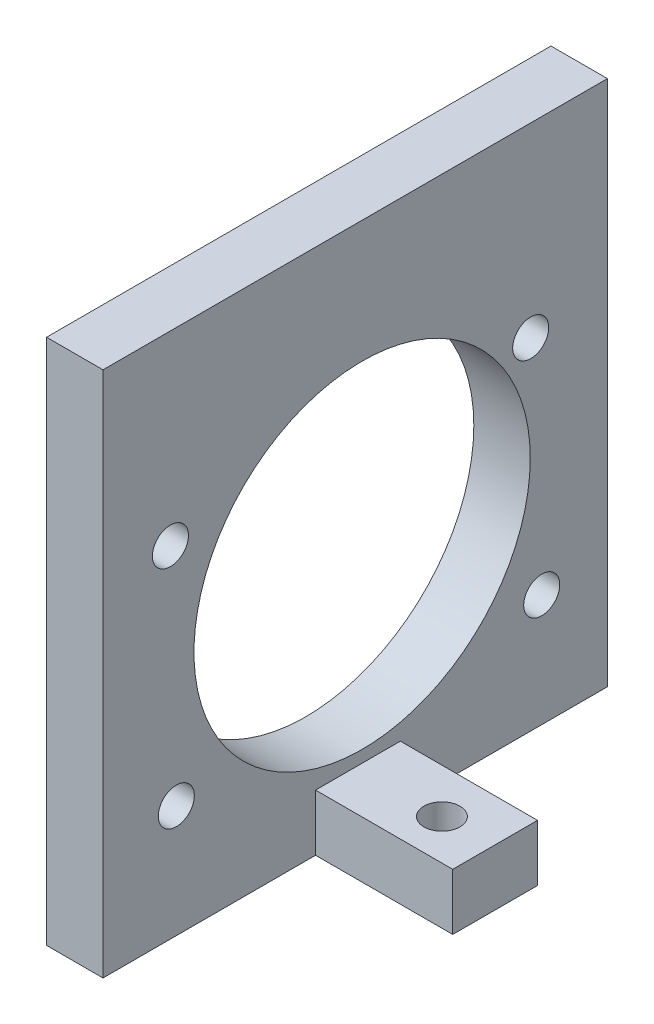
SolidWorks part; units mm, degrees
ref_plane "Front Plane" through (0, 0, 0) normal (0, 0, 1) x (1, 0, 0)
ref_plane "Top Plane" through (0, 0, 0) normal (0, 1, 0) x (1, 0, 0)
ref_plane "Right Plane" through (0, 0, 0) normal (1, 0, 0) x (0, 0, -1)
sketch "Sketch1" plane through (0, 0, 0) normal (0, 0, 1) x (1, 0, 0)
  line L0 (0, 0) -> (0, 39.1564)
  line L1 (0, 0) -> (16.4406, 0)
  dimension "D1" = 39.1564
  dimension "D2" = 16.4406
extrude "Extrude-Thin2" add sketch "Sketch1" against normal blind 42 thin thin type one direction wall 4.7
sketch "Sketch2" plane through (0, 0, 0) normal (0, 1, 0) x (1, 0, 0)
  circle A0 centre (7.1662, 21.0521) radius 1.5
  dimension "D1" = 3
extrude "Cut-Extrude1" cut sketch "Sketch2" against normal through all
sketch "Sketch4" plane through (0, 0, 0) normal (1, 0, 0) x (0, 0, -1)
  circle A0 centre (21.575, 14.9958) radius 14
  dimension "D1" = 28
extrude "Cut-Extrude3" cut sketch "Sketch4" against normal through all
sketch "Sketch6" plane through (0, 0, 0) normal (1, 0, 0) x (0, 0, -1)
  circle A0 centre (5.6121, 23.6597) radius 1.5
  circle A1 centre (6.1013, 4.6597) radius 1.5
  circle A2 centre (35.6121, 23.6597) radius 1.5
  circle A3 centre (36.5295, 4.6597) radius 1.5
  dimension "D1" = 3
  dimension "D2" = 3
  dimension "D3" = 3
  dimension "D4" = 3
  dimension "D5" = 19
  dimension "D6" = 19
  dimension "D7" = 30
extrude "Cut-Extrude5" cut sketch "Sketch6" against normal through all
sketch "Sketch7" plane through (0, 0, 0) normal (0, 1, 0) x (1, 0, 0)
  line L0 (0, 42) -> (0, 0) construction
  line L1 (0, 17.6984) -> (16.4406, 17.6984)
  line L2 (0, 17.6984) -> (0, 0)
  line L3 (0, 0) -> (16.4406, 0)
  line L4 (16.4406, 17.6984) -> (16.4406, 0)
  line L5 (16.4406, 42) -> (16.4406, 0) construction
  line L6 (0, 42) -> (16.4406, 42)
  line L7 (0, 42) -> (0, 24.7582)
  line L8 (0, 24.7582) -> (16.4406, 24.7582)
  line L9 (16.4406, 42) -> (16.4406, 24.7582)
extrude "Cut-Extrude6" cut sketch "Sketch7" against normal through all
sketch "Sketch8" plane through (0, 0, 0) normal (0, 1, 0) x (1, 0, 0)
  line L0 (0, 24.7582) -> (16.4406, 24.7582) construction
  line L1 (11.4209, 24.7582) -> (16.4406, 24.7582)
  line L2 (11.4209, 24.7582) -> (11.4209, 17.6984)
  line L3 (11.4209, 17.6984) -> (16.4406, 17.6984)
  line L4 (16.4406, 24.7582) -> (16.4406, 17.6984)
  line L5 (16.4406, 17.6984) -> (0, 17.6984) construction
extrude "Cut-Extrude7" cut sketch "Sketch8" against normal through all
